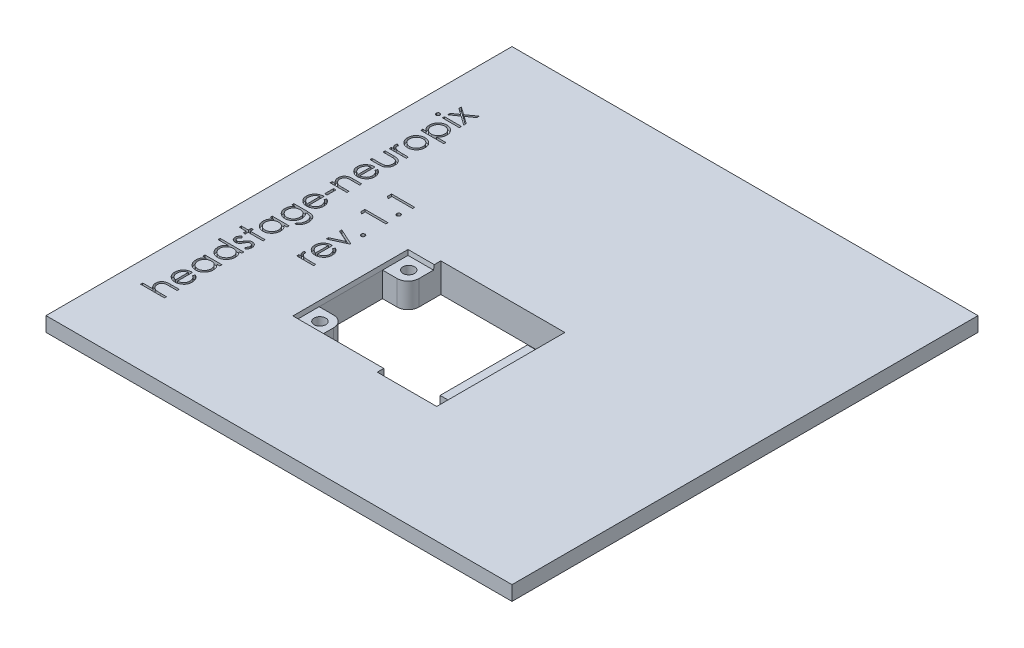
SolidWorks part; units mm, degrees
ref_plane "Front Plane" through (0, 0, 0) normal (0, 0, 1) x (1, 0, 0)
ref_plane "Top Plane" through (0, 0, 0) normal (0, 1, 0) x (1, 0, 0)
ref_plane "Right Plane" through (0, 0, 0) normal (1, 0, 0) x (0, 0, -1)
sketch "Sketch1" plane through (0, 0, 0) normal (0, 1, 0) x (1, 0, 0)
  line L1 (-32, 32) -> (32, 32)
  line L2 (-32, 32) -> (-32, -32)
  line L3 (-32, -32) -> (32, -32)
  line L4 (32, 32) -> (32, -32)
  line L5 (-32, 32) -> (32, -32) construction
  line L6 (-32, -32) -> (32, 32) construction
  point P0 (0, 0)
  dimension "D1" = 64
  dimension "D2" = 64
extrude "Boss-Extrude1" add sketch "Sketch1" along normal blind 4 contours L2 L3 L4 L1
sketch "Sketch2" plane through (0, 0, 0) normal (0, -1, 0) x (1, 0, 0)
  line L1 (-30, 30) -> (30, 30)
  line L2 (-30, 30) -> (-30, -30)
  line L3 (-30, -30) -> (30, -30)
  line L4 (30, 30) -> (30, -30)
  line L5 (-30, 30) -> (30, -30) construction
  line L6 (-30, -30) -> (30, 30) construction
  line L7 (32, 32) -> (-32, 32)
  line L8 (32, 32) -> (32, -32)
  line L9 (32, -32) -> (-32, -32)
  line L10 (-32, 32) -> (-32, -32)
  line L11 (32, 32) -> (-32, -32) construction
  line L12 (32, -32) -> (-32, 32) construction
  point P0 (0, 0)
  point P6 (0, 0)
  line M5 (-32, -32) -> (32, -32)
  line M6 (32, -32) -> (32, 32)
  line M7 (32, 32) -> (-32, 32)
  line M8 (-32, 32) -> (-32, -32)
  dimension "D1" = 2
  dimension "D2" = 2
extrude "Cut-Extrude1" cut sketch "Sketch2" against normal blind 2 contours L1 L4 L3 L2 M8 M5 M6 M7
sketch "Sketch4" plane through (0, 4, 0) normal (0, 1, 0) x (1, 0, 0)
  line L0 (4.3, -7.18) -> (-6.8945, -7.18) construction
  line L1 (-14.9, -14.98) -> (5.3, -14.98)
  line L2 (-14.9, -14.98) -> (-14.9, 0.62)
  line L3 (-14.9, 0.62) -> (5.3, 0.62)
  line L4 (5.3, -14.98) -> (5.3, 0.62)
  point P4 (4.3, -7.18)
  point P8 (-13.1, -1.08)
  point P12 (-13.1, -13.28)
  dimension "D1" = 1
  dimension "D2" = 19.2
  dimension "D3" = 7.8
  dimension "D4" = 7.8
  dimension "D5" = 17.4
  dimension "D6" = 6.1
extrude "Cut-Extrude2" cut sketch "Sketch4" along normal blind 10 draft 10 from offset 0.6 contours L3 L4 L1 L2 offset against normal yes draft outward yes
hole_wizard "Tap Drill for M2x0.4 Tap1" positions "3DSketch1" profile "Sketch5" hole size "M2x0.4" standard "ANSI Metric" end condition through all
sketch3d "3DSketch1"
  point P0 (-13.1, 4, 13.28)
  point P3 (-13.1, 4, 1.08)
sketch "Sketch5" plane through (-13.1, 4, 13.28) normal (1, 0, 0) x (0, 0, 1)
  line L0 (0, 0) -> (0, 4)
  line L1 (0, 4) -> (0.8, 4)
  line L2 (0.8, 4) -> (0.8, 0)
  line L5 (0.8, 0) -> (0, 0)
  line L11 (0, -6.35) -> (0, 107.95) construction
  dimension "Thru Hole Dia." = 1.6
  dimension "Thru Hole Depth" = 4
sketch "Sketch11" plane through (0, 3.4, 0) normal (0, 1, 0) x (1, 0, 0)
  line L0 (-14.9, -11.5858) -> (-12.9, -11.5858)
  line L1 (-14.9, -14.98) -> (-14.9, 0.62) construction
  line L2 (-11.4, -13.0858) -> (-11.4, -14.5858)
  line L3 (-6.5324, -15.0858) -> (-2.5257, -15.0858)
  line L4 (-2.5257, -15.0858) -> (-2.5257, -15.98)
  line L5 (-2.5257, -15.98) -> (5.6369, -15.98)
  line L6 (5.6369, -15.98) -> (5.6369, 1.62)
  line L7 (5.6369, 1.62) -> (-11.4, 1.62)
  line L8 (-11.4, 1.62) -> (-11.4, -1.38)
  line L9 (-12.9, -2.88) -> (-14.9, -2.88)
  line L10 (-14.9, -2.88) -> (-14.9, -11.5858)
  line L11 (-14.9, 0.62) -> (5.3, 0.62) construction
  line L12 (-15.0058, -15.0858) -> (5.4058, -15.0858) construction
  line L13 (-11.4, -14.5858) -> (-6.5324, -14.5858)
  line L14 (-6.5324, -14.5858) -> (-6.5324, -15.0858)
  line L15 (-14.9, -14.98) -> (5.3, -14.98) construction
  arc A0 (-11.4, -13.0858) -> (-12.9, -11.5858) centre (-12.9, -13.0858) ccw
  arc A1 (-11.4, -1.38) -> (-12.9, -2.88) centre (-12.9, -1.38) cw
  point P14 (-11.4, -11.5858)
  dimension "D3" = 1.5
  dimension "D5" = 1.5
  dimension "D1" = 3.5
  dimension "D2" = 1
  dimension "D4" = 3.5
  dimension "D6" = 1
  dimension "D7" = 0.5
extrude "Cut-Extrude4" cut sketch "Sketch11" against normal through all and the other way through all
sketch "Sketch12" plane through (0, 0, 0) normal (0, 1, 0) x (1, 0, 0)
  line L0 (4.3, -7.18) -> (-6.8945, -7.18) construction
  line L1 (3.303, -13.18) -> (6.4277, -13.18)
  line L2 (3.303, -13.18) -> (3.303, -1.18)
  line L3 (3.303, -1.18) -> (6.4277, -1.18)
  line L4 (6.4277, -13.18) -> (6.4277, -1.18)
  point P4 (6.4277, -7.18)
  dimension "D1" = 12
extrude "Boss-Extrude2" add sketch "Sketch12" along normal offset from surface (2.75 mm away) 1.25 up to face at (-5.9024, 4, 8.0584)
sketch "Sketch13" plane through (0, 4, 0) normal (0, 1, 0) x (1, 0, 0)
  line L0 (-25.9753, -25.694) -> (-25.9753, 25.0231) construction
  text T0 "headstage-neuropix\r\nrev. 1.1"
extrude "Cut-Extrude5" cut sketch "Sketch13" against normal blind 0.5
thread "Thread1" [suppressed] pitch 0.4 start angle 0, offset 1, length 0, pitch 0.4, diameter 1.6
ref_plane "Plane1" through (-13.9, 4.4, 1.08) normal (0, 0, 1) x (-1, 0, 0)
sketch "Thread Profile1" plane through (-13.9, 4.4, 1.08) normal (0, 0, 1) x (-1, 0, 0)
  line L0 (0, 0) -> (0, 0.4) construction
  line L1 (0, 0) -> (0.2165, 0.125)
  line L2 (0.2165, 0.125) -> (0.2165, 0.175)
  line L3 (0.2165, 0.175) -> (0, 0.3)
  line L4 (0.2165, 0.15) -> (0, 0.15) construction
  line L11 (0, 0) -> (0, 0.3)
  point P2 (0, 0)
  dimension "Pitch" = 0.4
  dimension "Profile_Angle" = 60
  dimension "Profile_Land" = 0.05
  dimension "Profile_Height" = 0.2165
thread "Thread2" [suppressed] pitch 0.4 start angle 0, offset 1, length 0, pitch 0.4, diameter 1.6
ref_plane "Plane2" through (-13.9, 4.4, 13.28) normal (0, 0, 1) x (-1, 0, 0)
sketch "Thread Profile2" plane through (-13.9, 4.4, 13.28) normal (0, 0, 1) x (-1, 0, 0)
  line L0 (0, 0) -> (0, 0.4) construction
  line L1 (0, 0) -> (0.2165, 0.125)
  line L2 (0.2165, 0.125) -> (0.2165, 0.175)
  line L3 (0.2165, 0.175) -> (0, 0.3)
  line L4 (0.2165, 0.15) -> (0, 0.15) construction
  line L11 (0, 0) -> (0, 0.3)
  point P2 (0, 0)
  dimension "Pitch" = 0.4
  dimension "Profile_Angle" = 60
  dimension "Profile_Land" = 0.05
  dimension "Profile_Height" = 0.2165
sketch "Sketch10" plane through (0, 3.4, 0) normal (0, 1, 0) x (1, 0, 0)
  circle A0 centre (-13.1, -13.28) radius 1.1
  circle A1 centre (-13.1, -1.08) radius 1.1
  dimension "D1" = 2.2
  dimension "D2" = 2.2
extrude "Cut-Extrude3" [suppressed] cut sketch "Sketch10" against normal blind 10 draft 45
